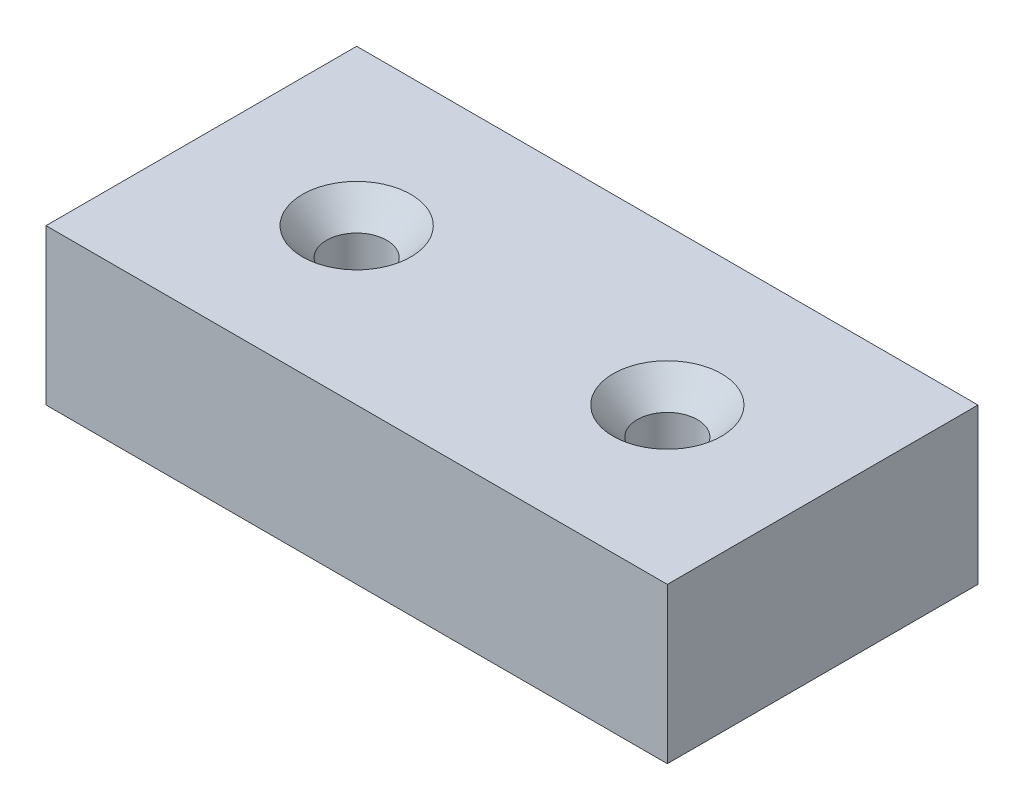
SolidWorks part; units mm, degrees
material "Ductile Iron"
ref_plane "Front Plane" through (0, 0, 0) normal (0, 0, 1) x (1, 0, 0)
ref_plane "Top Plane" through (0, 0, 0) normal (0, 1, 0) x (1, 0, 0)
ref_plane "Right Plane" through (0, 0, 0) normal (1, 0, 0) x (0, 0, -1)
ref_plane "Plane1" through (0, 6.35, 0) normal (0, 1, 0) x (1, 0, 0)
sketch "Sketch1" plane through (0, 6.35, 0) normal (0, 1, 0) x (1, 0, 0)
  line L0 (25.4, -12.7) -> (25.4, 12.7)
  line L1 (25.4, 12.7) -> (-25.4, 12.7)
  line L2 (-25.4, 12.7) -> (-25.4, -12.7)
  line L3 (-25.4, -12.7) -> (25.4, -12.7)
extrude "Boss-Extrude1" add sketch "Sketch1" against normal blind 12.7
hole_wizard "Hole1" positions "Sketch3" profile "Sketch2" legacy
sketch "Sketch3" plane through (0, 6.35, 0) normal (0, 1, 0) x (1, 0, 0)
  point P0 (-12.7, 0)
  point P1 (12.7, 0)
sketch "Sketch2" plane through (-12.7, 6.35, 0) normal (1, 0, 0) x (0, 0, 1)
  line L0 (0, 0) -> (0, 12.7)
  line L1 (0, 12.7) -> (2.4638, 12.7)
  line L2 (2.4638, 12.7) -> (2.4638, 0)
  line L3 (2.4638, 0) -> (0, 0)
  line L4 (0, 110) -> (0, -10) construction
  dimension "Diameter" = 4.9276
  dimension "Depth" = 12.7
chamfer "Chamfer1" distance 1.9685 angle 49 4 edges at (12.7, -6.35, 2.4638) (-12.7, -6.35, 2.4638) (-12.7, 6.35, 2.4638) (12.7, 6.35, 2.4638)
